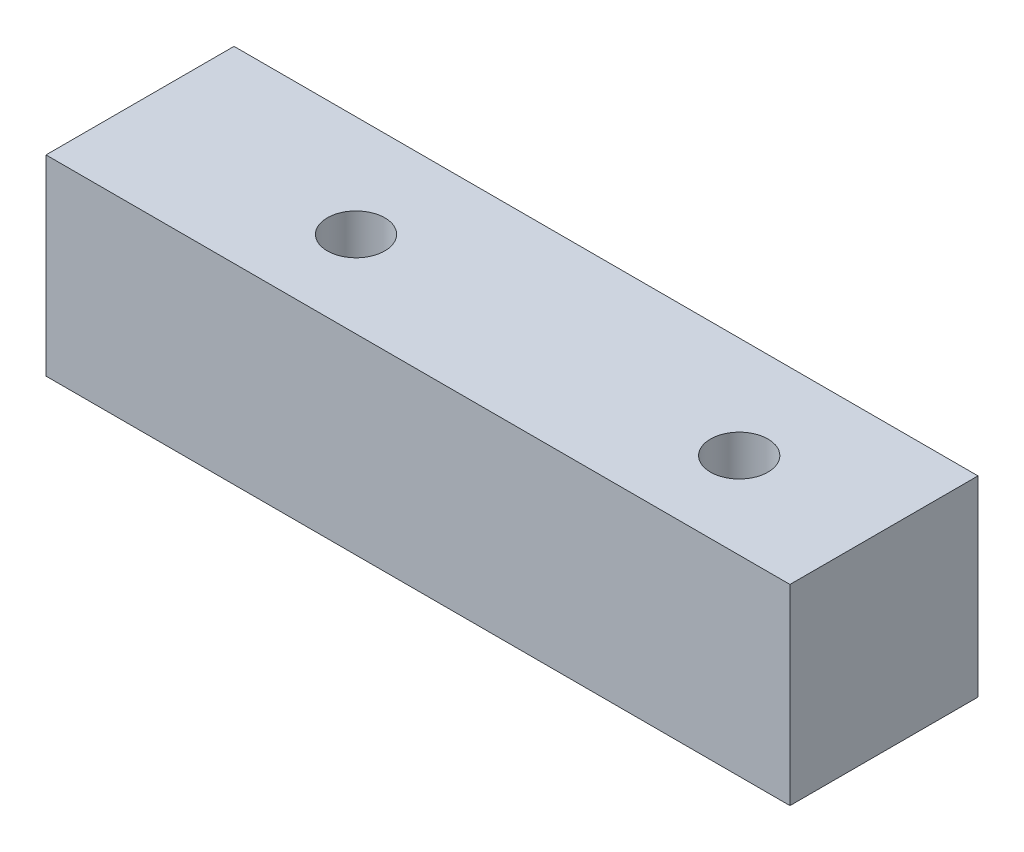
SolidWorks part; units mm, degrees
ref_plane "前视基准面" through (0, 0, 0) normal (0, 0, 1) x (1, 0, 0)
ref_plane "上视基准面" through (0, 0, 0) normal (0, 1, 0) x (1, 0, 0)
ref_plane "右视基准面" through (0, 0, 0) normal (1, 0, 0) x (0, 0, -1)
other "Configuration Table"
sketch "草图1" plane through (0, 0, 0) normal (0, 1, 0) x (1, 0, 0)
  line L1 (-26.6694, 7.065) -> (12.1622, 7.065)
  line L2 (-26.6694, 7.065) -> (-26.6694, -2.7495)
  line L3 (-26.6694, -2.7495) -> (12.1622, -2.7495)
  line L4 (12.1622, 7.065) -> (12.1622, -2.7495)
  line L5 (-26.6694, 7.065) -> (12.1622, -2.7495) construction
  line L6 (-26.6694, -2.7495) -> (12.1622, 7.065) construction
  circle A0 centre (-14.9865, 1.7505) radius 1.5
  circle A1 centre (5.0135, 1.7505) radius 1.5
  point P0 (-7.2536, 2.1577)
  dimension "D1" = 3
  dimension "D2" = 3
  dimension "D3" = 20
  dimension "D4" = 4.5
  dimension "D5" = 4.5
extrude "凸台-拉伸1" add sketch "草图1" along normal blind 10
